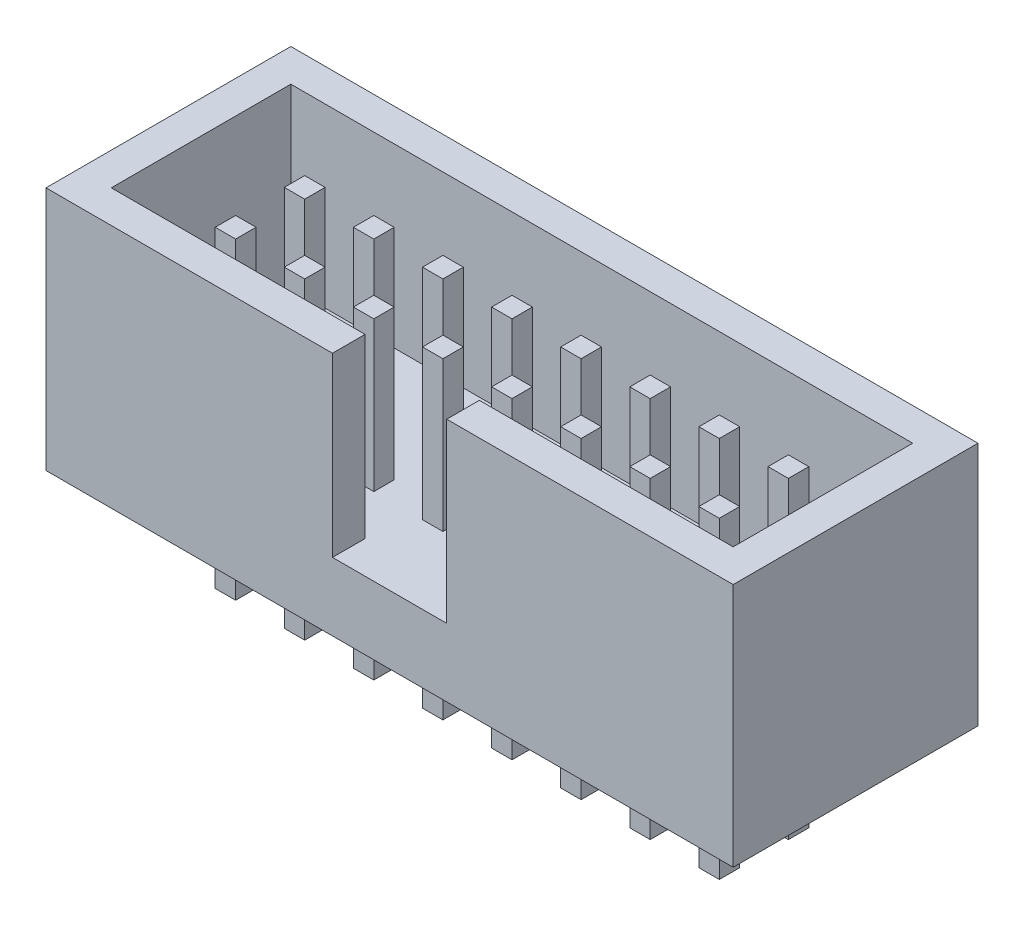
SolidWorks part; units mm, degrees
ref_plane "前视基准面" through (0, 0, 0) normal (0, 0, 1) x (1, 0, 0)
ref_plane "上视基准面" through (0, 0, 0) normal (0, 1, 0) x (1, 0, 0)
ref_plane "右视基准面" through (0, 0, 0) normal (1, 0, 0) x (0, 0, -1)
sketch "草图1" plane through (0, 0, 0) normal (0, 1, 0) x (1, 0, 0)
  line L0 (0, 85.0964) -> (0, -118.2031) construction
  line L1 (-12.63, 4.5) -> (12.63, 4.5)
  line L2 (-12.63, 4.5) -> (-12.63, -4.5)
  line L3 (-12.63, -4.5) -> (12.63, -4.5)
  line L4 (12.63, 4.5) -> (12.63, -4.5)
  line L5 (-200.5452, 0) -> (261.2352, 0) construction
  dimension "D1" = 9
  dimension "D2" = 25.26
extrude "拉伸1" add sketch "草图1" along normal blind 9
sketch "草图2" plane through (0, 9, 0) normal (0, 1, 0) x (-1, 0, 0)
  line L8 (-11.43, 3.3) -> (-11.43, -3.3)
  line L9 (11.43, 3.3) -> (-11.43, 3.3)
  line L10 (11.43, -3.3) -> (11.43, 3.3)
  line L11 (-11.43, -3.3) -> (11.43, -3.3)
  line L12 (-11.43, 3.3) -> (-11.43, -3.3)
  line L13 (11.43, 3.3) -> (-11.43, 3.3)
  line L14 (11.43, -3.3) -> (11.43, 3.3)
  line L15 (-11.43, -3.3) -> (11.43, -3.3)
  dimension "D1" = 1.2
extrude "切除-拉伸1" cut sketch "草图2" against normal blind 6.5
sketch "草图3" plane through (0, 0, 4.5) normal (0, 0, 1) x (1, 0, 0)
  line L0 (-12.63, 9) -> (12.63, 9) construction
  line L1 (-2.1, 9) -> (2.1, 9)
  line L2 (-2.1, 9) -> (-2.1, 2.5)
  line L3 (-2.1, 2.5) -> (2.1, 2.5)
  line L4 (2.1, 9) -> (2.1, 2.5)
  line L5 (-11.43, 2.5) -> (11.43, 2.5) construction
  line L6 (0, 9.4226) -> (0, -4.0288) construction
  dimension "D1" = 4.2
extrude "切除-拉伸2" cut sketch "草图3" against normal blind 6.5
sketch "草图5" plane through (0, 0, 0) normal (0, -1, 0) x (1, 0, 0)
  line L0 (0, 6.0683) -> (0, -6.9786) construction
  line L1 (-14.7999, 0) -> (15.2382, 0) construction
  line L2 (-1.27, 2.5244) -> (-1.27, -0.4442) construction
  line L3 (-1.645, 0.895) -> (-0.895, 0.895)
  line L4 (-1.645, 0.895) -> (-1.645, 1.645)
  line L5 (-1.645, 1.645) -> (-0.895, 1.645)
  line L6 (-0.895, 0.895) -> (-0.895, 1.645)
  line L7 (-2.3518, 1.27) -> (0.5396, 1.27) construction
  line L8 (-4.185, 0.895) -> (-3.435, 0.895)
  line L9 (-4.185, 0.895) -> (-4.185, 1.645)
  line L10 (-4.185, 1.645) -> (-3.435, 1.645)
  line L11 (-3.435, 0.895) -> (-3.435, 1.645)
  line L12 (-6.725, 0.895) -> (-5.975, 0.895)
  line L13 (-6.725, 0.895) -> (-6.725, 1.645)
  line L14 (-6.725, 1.645) -> (-5.975, 1.645)
  line L15 (-5.975, 0.895) -> (-5.975, 1.645)
  line L16 (-9.265, 0.895) -> (-8.515, 0.895)
  line L17 (-9.265, 0.895) -> (-9.265, 1.645)
  line L18 (-9.265, 1.645) -> (-8.515, 1.645)
  line L19 (-8.515, 0.895) -> (-8.515, 1.645)
  line L20 (-8.515, -0.895) -> (-8.515, -1.645)
  line L21 (-9.265, -1.645) -> (-8.515, -1.645)
  line L22 (-9.265, -0.895) -> (-9.265, -1.645)
  line L23 (-9.265, -0.895) -> (-8.515, -0.895)
  line L24 (-5.975, -0.895) -> (-5.975, -1.645)
  line L25 (-6.725, -1.645) -> (-5.975, -1.645)
  line L26 (-6.725, -0.895) -> (-6.725, -1.645)
  line L27 (-6.725, -0.895) -> (-5.975, -0.895)
  line L28 (-3.435, -0.895) -> (-3.435, -1.645)
  line L29 (-4.185, -1.645) -> (-3.435, -1.645)
  line L30 (-4.185, -0.895) -> (-4.185, -1.645)
  line L31 (-4.185, -0.895) -> (-3.435, -0.895)
  line L32 (-0.895, -0.895) -> (-0.895, -1.645)
  line L33 (-1.645, -1.645) -> (-0.895, -1.645)
  line L34 (-1.645, -0.895) -> (-1.645, -1.645)
  line L35 (-1.645, -0.895) -> (-0.895, -0.895)
  line L36 (1.27, 2.5244) -> (1.27, -0.4442) construction
  line L37 (1.645, -0.895) -> (0.895, -0.895)
  line L38 (1.645, -0.895) -> (1.645, -1.645)
  line L39 (1.645, -1.645) -> (0.895, -1.645)
  line L40 (0.895, -0.895) -> (0.895, -1.645)
  line L41 (4.185, -0.895) -> (3.435, -0.895)
  line L42 (4.185, -0.895) -> (4.185, -1.645)
  line L43 (4.185, -1.645) -> (3.435, -1.645)
  line L44 (3.435, -0.895) -> (3.435, -1.645)
  line L45 (6.725, -0.895) -> (5.975, -0.895)
  line L46 (6.725, -0.895) -> (6.725, -1.645)
  line L47 (6.725, -1.645) -> (5.975, -1.645)
  line L48 (5.975, -0.895) -> (5.975, -1.645)
  line L49 (9.265, -0.895) -> (8.515, -0.895)
  line L50 (9.265, -0.895) -> (9.265, -1.645)
  line L51 (9.265, -1.645) -> (8.515, -1.645)
  line L52 (8.515, -0.895) -> (8.515, -1.645)
  line L53 (8.515, 0.895) -> (8.515, 1.645)
  line L54 (9.265, 1.645) -> (8.515, 1.645)
  line L55 (9.265, 0.895) -> (9.265, 1.645)
  line L56 (9.265, 0.895) -> (8.515, 0.895)
  line L57 (5.975, 0.895) -> (5.975, 1.645)
  line L58 (6.725, 1.645) -> (5.975, 1.645)
  line L59 (6.725, 0.895) -> (6.725, 1.645)
  line L60 (6.725, 0.895) -> (5.975, 0.895)
  line L61 (3.435, 0.895) -> (3.435, 1.645)
  line L62 (4.185, 1.645) -> (3.435, 1.645)
  line L63 (4.185, 0.895) -> (4.185, 1.645)
  line L64 (4.185, 0.895) -> (3.435, 0.895)
  line L65 (0.895, 0.895) -> (0.895, 1.645)
  line L66 (1.645, 1.645) -> (0.895, 1.645)
  line L67 (1.645, 0.895) -> (1.645, 1.645)
  line L68 (1.645, 0.895) -> (0.895, 0.895)
  dimension "D1" = 0.75
  dimension "D2" = 0.75
  dimension "D3" = 1.27
  dimension "D4" = 1.27
extrude "拉伸2" add sketch "草图5" along normal blind 3.5 and the other way offset from surface (8 mm away) 1 other way up to face at (0, 9, 1.3)
sketch "草图6" plane through (0, 0, 0) normal (0, -1, 0) x (1, 0, 0)
  line L0 (14.8773, 0) -> (-15.139, 0) construction
  line L1 (0, 6.7624) -> (0, -6.108) construction
  line L6 (-8.515, 1.645) -> (-9.265, 1.645) construction
  line L8 (-9.265, 1.645) -> (-9.265, 0.895) construction
  line L9 (-9.265, 0.895) -> (-8.515, 0.895) construction
  circle A0 centre (-8.89, 1.27) radius 0.375
